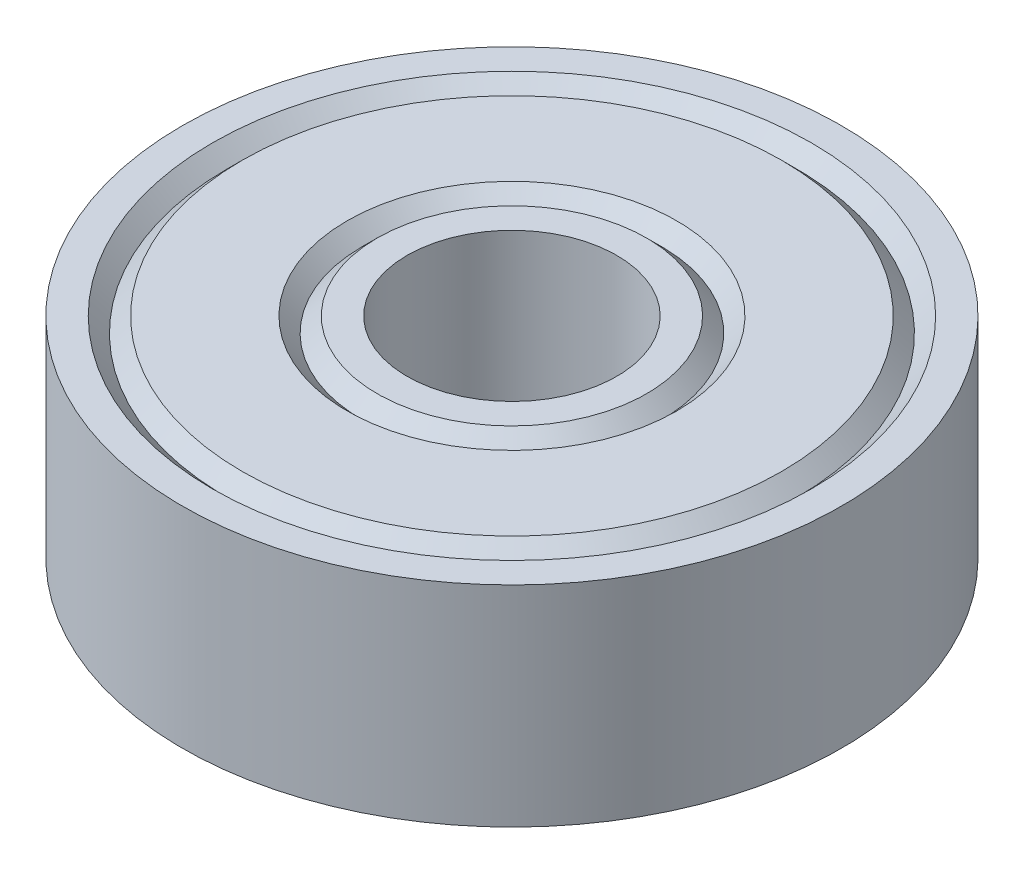
SolidWorks part; units mm, degrees
ref_plane "Front Plane" through (0, 0, 0) normal (0, 0, 1) x (1, 0, 0)
ref_plane "Top Plane" through (0, 0, 0) normal (0, 1, 0) x (1, 0, 0)
ref_plane "Right Plane" through (0, 0, 0) normal (1, 0, 0) x (0, 0, -1)
sketch "Sketch1" plane through (0, 0, 0) normal (0, 0, 1) x (1, 0, 0)
  line L0 (0, 3.5) -> (0, -3.5) construction
  line L1 (-3.5, 3.5) -> (-4.5, 3.5)
  line L2 (-3.5, 3.5) -> (-3.5, -3.5)
  line L3 (-3.5, -3.5) -> (-4.5, -3.5)
  line L4 (-11, 3.5) -> (-11, -3.5)
  line L5 (-10, 3.5) -> (-9.5, 3)
  line L6 (-9.5, 3) -> (-9, 3.5)
  line L7 (-5.5, 3.5) -> (-5, 3)
  line L8 (-5, 3) -> (-4.5, 3.5)
  line L9 (-10, -3.5) -> (-9.5, -3)
  line L10 (-9.5, -3) -> (-9, -3.5)
  line L11 (-5.5, -3.5) -> (-5, -3)
  line L12 (-5, -3) -> (-4.5, -3.5)
  line L13 (-5.5, -3.5) -> (-9, -3.5)
  line L14 (-10, -3.5) -> (-11, -3.5)
  line L15 (-10, 3.5) -> (-11, 3.5)
  line L16 (-5.5, 3.5) -> (-9, 3.5)
  line L17 (-9.5, 3) -> (-5, 3) construction
  line L18 (-9.5, 3) -> (-9.5, -3) construction
  line L19 (-5, -3) -> (-9.5, -3) construction
  line L20 (-5, 3) -> (-5, -3) construction
  line L21 (-9.5, 0) -> (-8, 0) construction
  line L22 (-4.5, 3.5) -> (-5.5, 3.5) construction
  line L23 (-8, 0) -> (-6.5, 0) construction
  line L24 (-9.5, 0) -> (-11, 0) construction
  line L25 (-6.5, 0) -> (-5, 0) construction
  line L26 (-5, 0) -> (-3.5, 0) construction
  dimension "D1" = 7
  dimension "D2" = 7
  dimension "D3" = 22
revolve "Revolve1" add sketch "Sketch1" angle 360 about L0
